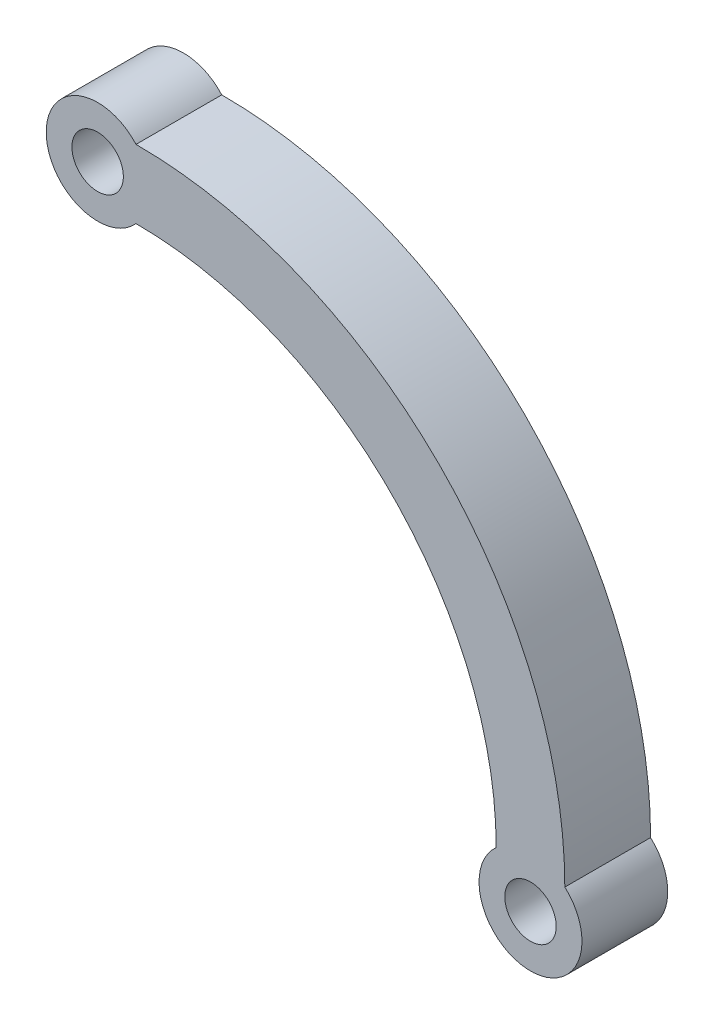
SolidWorks part; units mm, degrees
ref_plane "Front" through (0, 0, 0) normal (0, 0, 1) x (1, 0, 0)
ref_plane "Top" through (0, 0, 0) normal (0, 1, 0) x (1, 0, 0)
ref_plane "Right" through (0, 0, 0) normal (1, 0, 0) x (0, 0, -1)
sketch "Esquisse1" plane through (0, 0, 0) normal (0, 0, 1) x (1, 0, 0)
  line L0 (0, 42) -> (0, 50)
  line L1 (42, 0) -> (50, 0)
  line L2 (0, 42) -> (0, 0) construction
  line L3 (0, 0) -> (42, 0) construction
  arc A0 (42, 0) -> (0, 42) centre (0, 0) ccw
  arc A1 (50, 0) -> (0, 50) centre (0, 0) ccw
  dimension "D1" = 42
  dimension "D2" = 8
extrude "Boss.-Extru.1" add sketch "Esquisse1" along normal blind 10
sketch "Esquisse2" plane through (0, 0, 10) normal (0, 0, 1) x (1, 0, 0)
  line L0 (0, 42) -> (0, 50)
  line L1 (0, 0) -> (29.6985, 29.6985) construction
  line L2 (42, 0) -> (50, 0)
  arc A0 (0, 42) -> (0, 50) centre (-4.4721, 46) cw
  arc A1 (42, 0) -> (0, 42) centre (0, 0) ccw construction
  arc A2 (42, 0) -> (50, 0) centre (46, -4.4721) ccw
  dimension "D1" = 6
extrude "Boss.-Extru.2" add sketch "Esquisse2" against normal up to vertex (10 mm away) up to point (50, 0, 0)
sketch "Esquisse3" plane through (0, 0, 10) normal (0, 0, 1) x (1, 0, 0)
  circle A0 centre (46, -4.4721) radius 3
  circle A1 centre (-4.4721, 46) radius 3
  dimension "D1" = 6
extrude "Enlèv. mat.-Extru.1" cut sketch "Esquisse3" against normal up to vertex (10 mm away) up to point (50, 0, 0)
